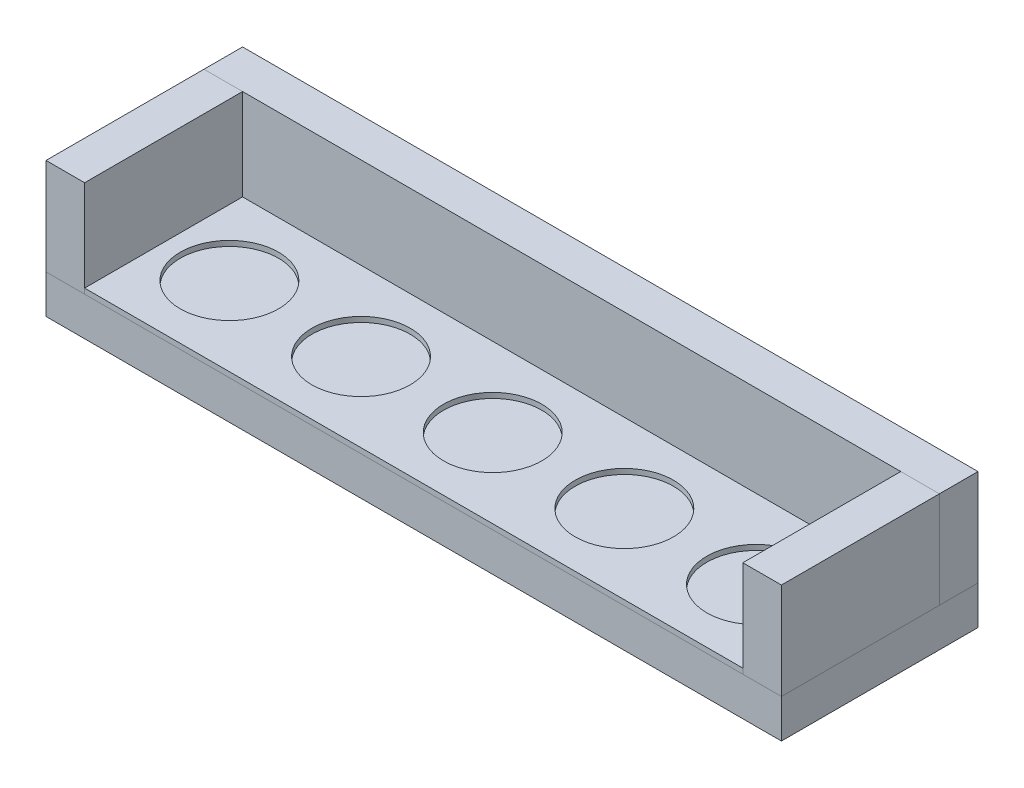
SolidWorks part; units mm, degrees
material "Pin"
ref_plane "Plan de face" through (0, 0, 0) normal (0, 0, 1) x (1, 0, 0)
ref_plane "Plan de dessus" through (0, 0, 0) normal (0, 1, 0) x (1, 0, 0)
ref_plane "Plan de droite" through (0, 0, 0) normal (1, 0, 0) x (0, 0, -1)
sketch "Esquisse1" plane through (0, 0, 0) normal (0, 1, 0) x (1, 0, 0)
  line L1 (-209.5, 112) -> (209.5, 112)
  line L2 (-209.5, 112) -> (-209.5, 0)
  line L3 (-209.5, 0) -> (209.5, 0)
  line L4 (209.5, 112) -> (209.5, 0)
  dimension "D1" = 112
  dimension "D2" = 419
extrude "Boss.-Extru.1" add sketch "Esquisse1" along normal blind 22
sketch "Esquisse2" plane through (0, 22, 0) normal (0, 1, 0) x (1, 0, 0)
  line L0 (209.5, 0) -> (209.5, 112) construction
  line L1 (-209.5, 112) -> (209.5, 112)
  line L2 (-209.5, 112) -> (-209.5, 90)
  line L3 (-209.5, 90) -> (209.5, 90)
  line L4 (209.5, 112) -> (209.5, 90)
  dimension "D1" = 22
extrude "Boss.-Extru.2" add sketch "Esquisse2" along normal blind 55 separate body
sketch "Esquisse3" plane through (0, 22, 0) normal (0, 1, 0) x (1, 0, 0)
  line L0 (-209.5, 90) -> (209.5, 90) construction
  line L1 (-209.5, 0) -> (-187.5, 0)
  line L2 (-209.5, 0) -> (-209.5, 90)
  line L3 (-209.5, 90) -> (-187.5, 90)
  line L4 (-187.5, 0) -> (-187.5, 90)
  line L5 (-209.5, 112) -> (-209.5, 90) construction
  line L6 (209.5, 0) -> (187.5, 0)
  line L7 (209.5, 0) -> (209.5, 90)
  line L8 (209.5, 90) -> (187.5, 90)
  line L9 (187.5, 0) -> (187.5, 90)
extrude "Boss.-Extru.3" add sketch "Esquisse3" along normal up to surface (55 mm away) separate body up to face at (0, 77, -101)
sketch "Esquisse4" plane through (0, 22, 0) normal (0, 1, 0) x (1, 0, 0)
  line L1 (-187.5, 0) -> (187.5, 0)
  line L2 (-187.5, 0) -> (-187.5, 90)
  line L3 (-187.5, 90) -> (187.5, 90)
  line L4 (187.5, 0) -> (187.5, 90)
  circle A0 centre (-150, 45) radius 28
  circle A1 centre (-75, 45) radius 28
  circle A2 centre (0, 45) radius 28
  circle A3 centre (75, 45) radius 28
  circle A4 centre (150, 45) radius 28
  dimension "D2" = 45
  dimension "D3" = 75
  dimension "D4" = 37.5
  dimension "D5" = 56
  dimension "D1" = 5
extrude "Boss.-Extru.4" add sketch "Esquisse4" along normal blind 3 separate body
